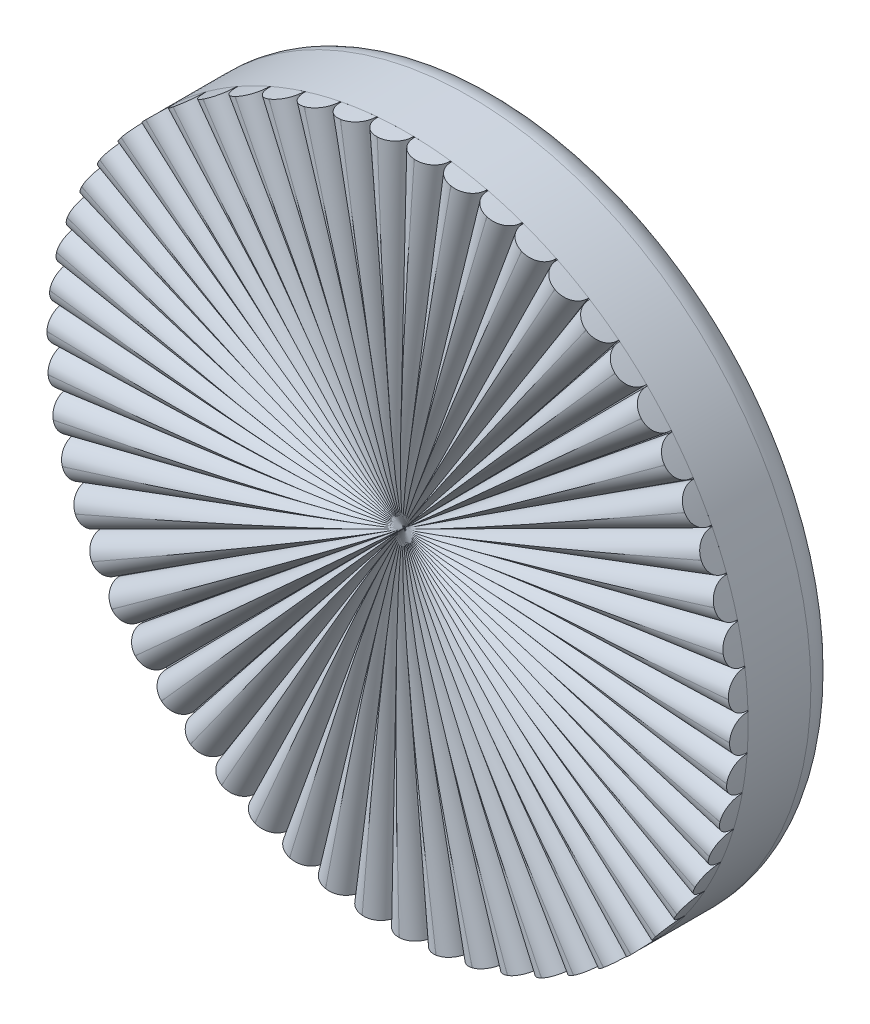
SolidWorks part; units mm, degrees
ref_plane "Front Plane" through (0, 0, 0) normal (0, 0, 1) x (1, 0, 0)
ref_plane "Top Plane" through (0, 0, 0) normal (0, 1, 0) x (1, 0, 0)
ref_plane "Right Plane" through (0, 0, 0) normal (1, 0, 0) x (0, 0, -1)
sketch "Sketch1" plane through (0, 0, 0) normal (0, 0, 1) x (1, 0, 0)
  circle A0 centre (0, 0) radius 92.5
  dimension "D1" = 185
extrude "Boss-Extrude1" add sketch "Sketch1" along normal blind 25
sketch "Sketch2" plane through (0, 0, 25) normal (0, 0, 1) x (1, 0, 0)
  line L0 (0, 0) -> (31.635, 86.9223)
  line L1 (0, 0) -> (40.5367, 83.1446)
  circle A0 centre (0, 0) radius 92.5 construction
  arc A1 (31.635, 86.9223) -> (40.5367, 83.1446) centre (0, 0) cw
extrude "Boss-Extrude2" add sketch "Sketch2" along normal blind 5 separate body
fillet "Fillet1" radius 4.75 2 edges at (20.2683, 41.5723, 30) (15.8175, 43.4611, 30)
pattern_circular "CirPattern1" count 58 over 360 about axis through (0, 0, 0) along (0, 0, 1) of bodies 102
fillet "Fillet2" radius 8 1 edges at (92.5, 0, 0)
